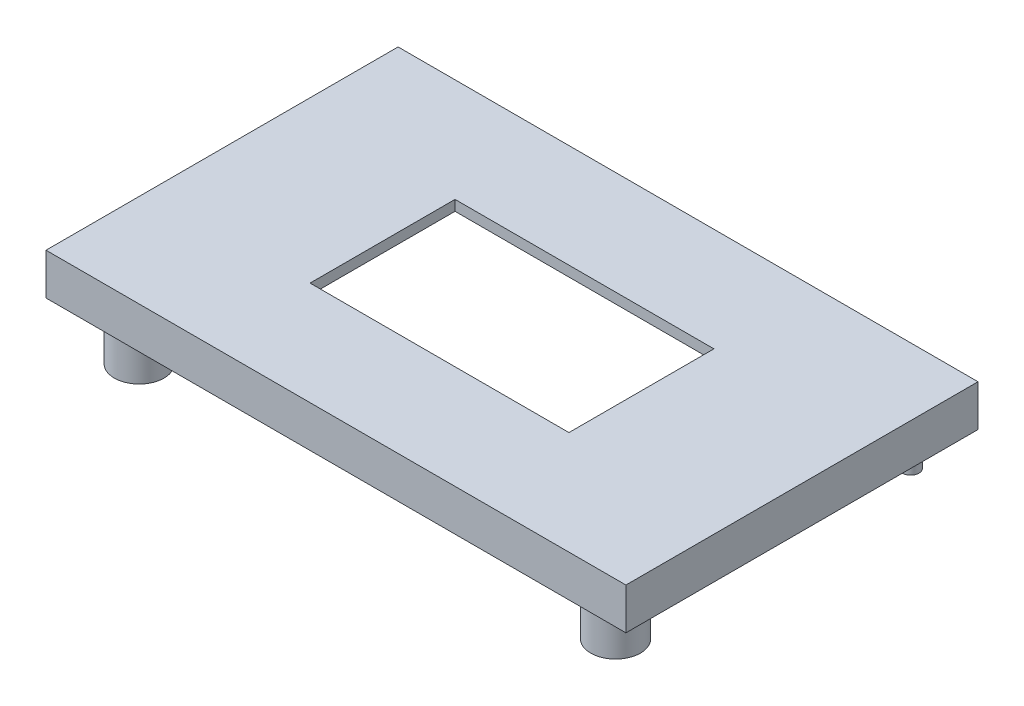
SolidWorks part; units mm, degrees
ref_plane "前视基准面" through (0, 0, 0) normal (0, 0, 1) x (1, 0, 0)
ref_plane "上视基准面" through (0, 0, 0) normal (0, 1, 0) x (1, 0, 0)
ref_plane "右视基准面" through (0, 0, 0) normal (1, 0, 0) x (0, 0, -1)
sketch "草图2" plane through (0, 0, 0) normal (0, 1, 0) x (1, 0, 0)
  line L0 (-20.168, 4.3174) -> (-20.168, -11.5892) construction
  line L1 (-21.168, 9.672) -> (34.832, 9.672)
  line L2 (-21.168, 9.672) -> (-21.168, -22.328)
  line L3 (-21.168, -22.328) -> (34.832, -22.328)
  line L4 (34.832, 9.672) -> (34.832, -22.328)
  line L5 (-20.168, 8.672) -> (33.832, 8.672)
  line L6 (-20.168, 8.672) -> (-20.168, -14.328)
  line L7 (-20.168, -14.328) -> (33.832, -14.328)
  line L8 (33.832, 8.672) -> (33.832, -14.328)
  line L9 (-7.168, -14.328) -> (20.832, -14.328)
  line L10 (-7.168, -14.328) -> (-7.168, -21.328)
  line L11 (-7.168, -21.328) -> (20.832, -21.328)
  line L12 (20.832, -14.328) -> (20.832, -21.328)
  line L13 (-21.168, 9.672) -> (34.832, 9.672)
  line L14 (34.832, -22.328) -> (-21.168, -22.328)
  line L15 (-20.168, 8.672) -> (33.832, 8.672)
  line L16 (33.832, -14.328) -> (20.832, -14.328)
  line L17 (20.832, -21.328) -> (-7.168, -21.328)
  line L18 (-7.168, -14.328) -> (-20.168, -14.328)
  dimension "D1" = 56
  dimension "D2" = 32
  dimension "D3" = 1
  dimension "D4" = 1
  dimension "D5" = 1
  dimension "D6" = 8
  dimension "D7" = 7
  dimension "D8" = 14
  dimension "D9" = 14
extrude "凸台-拉伸1" add sketch "草图2" along normal blind 3 contours L13 L0 L5 L8 L7 L12 L11 L10 L14 L4 | L0 L1 L2 L3 L6
ref_plane "基准面1" through (0, 3, 0) normal (0, 1, 0) x (1, 0, 0)
sketch "草图3" plane through (0, 3, 0) normal (0, 1, 0) x (1, 0, 0)
  line L0 (6.832, 9.672) -> (6.832, -22.328) construction
  line L1 (-21.168, 9.672) -> (34.832, 9.672)
  line L2 (-21.168, 9.672) -> (-21.168, -22.328)
  line L3 (-21.168, -22.328) -> (34.832, -22.328)
  line L4 (34.832, 9.672) -> (34.832, -22.328)
  line L9 (-20.168, 8.672) -> (33.832, 8.672) construction
  line L10 (19.332, -12.328) -> (-5.668, -12.328)
  line L11 (19.332, -12.328) -> (19.332, 1.672)
  line L12 (19.332, 1.672) -> (-5.668, 1.672)
  line L13 (-5.668, -12.328) -> (-5.668, 1.672)
  line L14 (19.332, -12.328) -> (-5.668, 1.672) construction
  line L15 (19.332, 1.672) -> (-5.668, -12.328) construction
  point P6 (6.832, -5.328)
  dimension "D1" = 25
  dimension "D2" = 14
  dimension "D3" = 7
extrude "凸台-拉伸2" add sketch "草图3" along normal blind 1
ref_plane "基准面2" through (0, 0, 0) normal (0, -1, 0) x (-1, 0, 0)
sketch "草图4" plane through (0, 0, 0) normal (0, -1, 0) x (-1, 0, 0)
  line L0 (17.5161, -14.328) -> (17.5161, -22.328) construction
  line L11 (20.168, -14.328) -> (7.168, -14.328) construction
  line L12 (21.168, -22.328) -> (-34.832, -22.328) construction
  line L13 (17.5161, -18.328) -> (7.9481, -18.328) construction
  line L14 (21.168, 9.672) -> (21.168, -22.328) construction
  line L15 (-34.832, 9.672) -> (-34.832, -22.328) construction
  circle A1 centre (16.168, -18.328) radius 2.4
  circle A2 centre (-29.832, -18.328) radius 2.4
  dimension "D1" = 5
  dimension "D2" = 5
ref_plane "基准面3" through (20.832, 0, 21.328) normal (1, 0, 0) x (0, 0, -1)
extrude "凸台-拉伸3" add sketch "草图4" along normal blind 5
ref_plane "基准面4" through (0, 4, 0) normal (0, -1, 0) x (-1, 0, 0)
sketch "草图6" plane through (0, 4, 0) normal (0, -1, 0) x (-1, 0, 0)
  line L1 (21.168, 9.672) -> (-34.832, 9.672)
  line L2 (21.168, 9.672) -> (21.168, 11.672)
  line L3 (21.168, 11.672) -> (-34.832, 11.672)
  line L4 (-34.832, 9.672) -> (-34.832, 11.672)
  dimension "D1" = 2
extrude "凸台-拉伸4" add sketch "草图6" along normal blind 4
sketch "草图7" plane through (0, 0, 0) normal (0, -1, 0) x (-1, 0, 0)
  line L0 (21.168, 11.672) -> (-34.832, 11.672) construction
  line L1 (-34.832, 11.672) -> (-34.832, -22.328) construction
  line L2 (21.168, 11.672) -> (21.168, -22.328) construction
  circle A0 centre (-29.832, 10.172) radius 0.8
  circle A1 centre (16.168, 10.172) radius 0.8
  dimension "D3" = 1.5
  dimension "D4" = 5
  dimension "D1" = 1.5
  dimension "D2" = 5
extrude "凸台-拉伸5" add sketch "草图7" along normal blind 5
